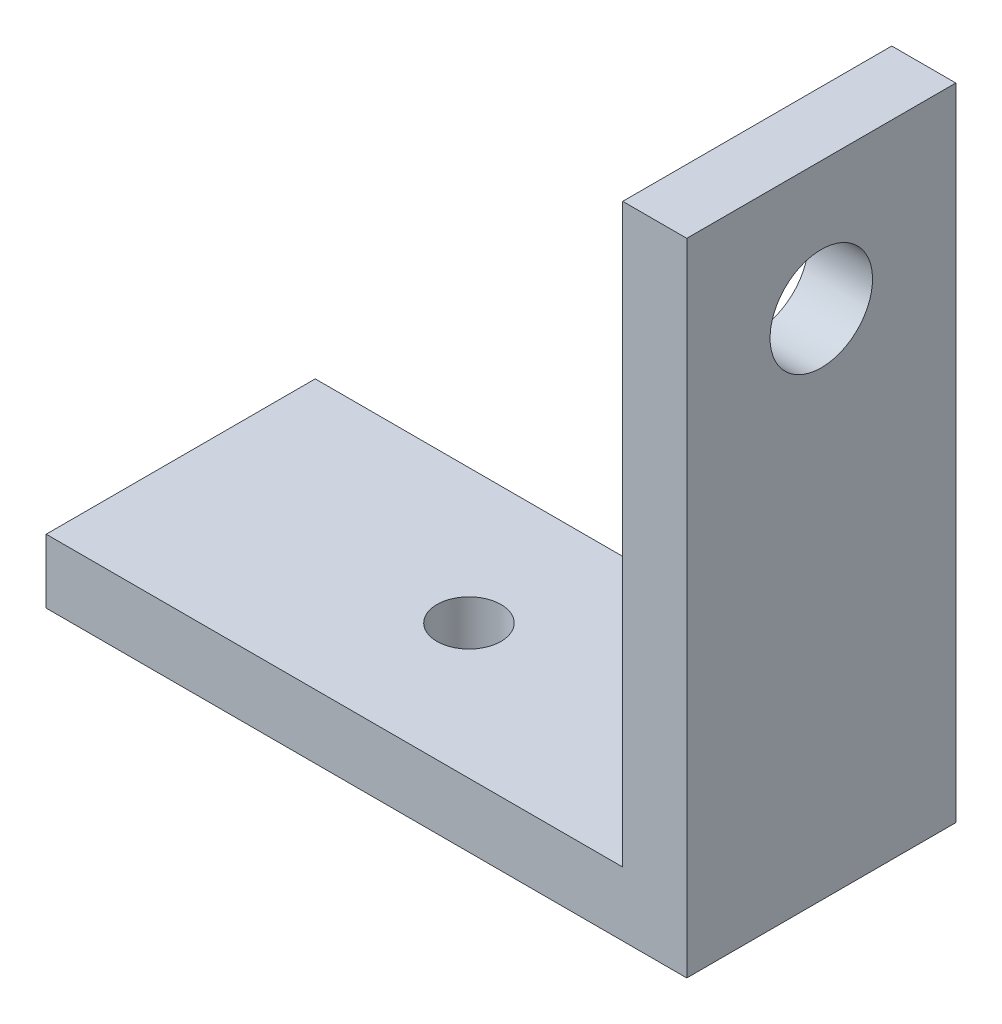
SolidWorks part; units mm, degrees
ref_plane "Front Plane" through (0, 0, 0) normal (0, 0, 1) x (1, 0, 0)
ref_plane "Top Plane" through (0, 0, 0) normal (0, 1, 0) x (1, 0, 0)
ref_plane "Right Plane" through (0, 0, 0) normal (1, 0, 0) x (0, 0, -1)
sketch "Sketch2" plane through (0, 0, 0) normal (0, 0, 1) x (1, 0, 0)
  line L0 (0, 0) -> (0, 50)
  line L1 (0, 50) -> (-5, 50)
  line L2 (-5, 50) -> (-5, 5)
  line L3 (-5, 5) -> (-50, 5)
  line L4 (-50, 5) -> (-50, 0)
  line L5 (-50, 0) -> (0, 0)
  dimension "D1" = 5
  dimension "D2" = 5
  dimension "D3" = 50
  dimension "D4" = 50
extrude "Boss-Extrude1" add sketch "Sketch2" along normal blind 21
sketch "Sketch3" plane through (-5, 0, 0) normal (-1, 0, 0) x (0, 0, 1)
  line L0 (21, 50) -> (21, 5) construction
  line L1 (21, 50) -> (0, 50) construction
  circle A0 centre (10.5, 40) radius 4
  dimension "D1" = 8
  dimension "D2" = 10.5
  dimension "D3" = 10
extrude "Cut-Extrude1" cut sketch "Sketch3" against normal through all
sketch "Sketch4" plane through (0, 0, 0) normal (0, 1, 0) x (1, 0, 0)
  line L0 (-5, -21) -> (-50, -21) construction
  line L2 (-50, -21) -> (-50, 0) construction
  circle A0 centre (-27.5, -10.5) radius 2.5
  dimension "D1" = 10.5
  dimension "D3" = 5
  dimension "D2" = 22.5
extrude "Cut-Extrude2" cut sketch "Sketch4" along normal through all contours A0
